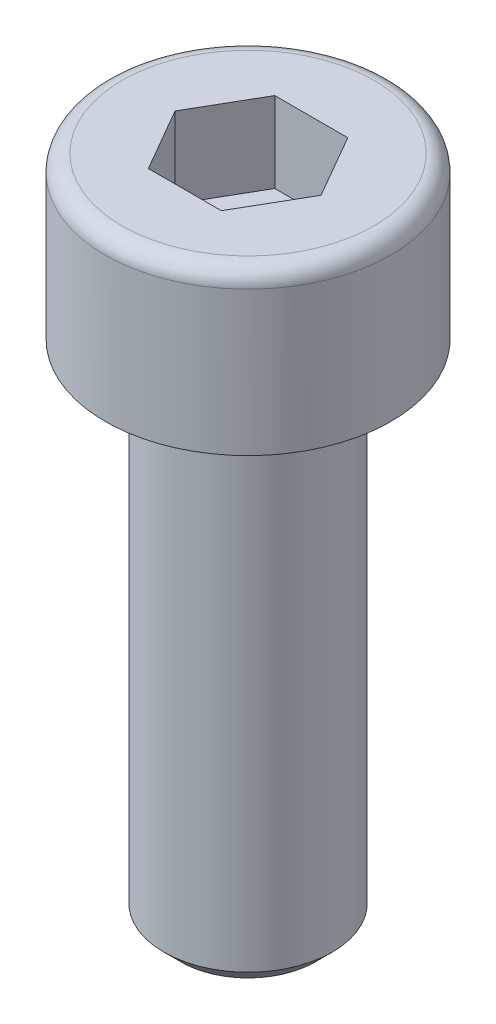
SolidWorks part; units mm, degrees
material "Cast Stainless Steel"
ref_plane "Front Plane" through (0, 0, 0) normal (0, 0, 1) x (1, 0, 0)
ref_plane "Top Plane" through (0, 0, 0) normal (0, 1, 0) x (1, 0, 0)
ref_plane "Right Plane" through (0, 0, 0) normal (1, 0, 0) x (0, 0, -1)
sketch "Sketch1" plane through (0, 0, 0) normal (0, 0, 1) x (1, 0, 0)
  line L0 (0, 0) -> (0, 3.82)
  line L1 (0, 3.82) -> (3.39, 3.82)
  line L2 (3.39, 3.82) -> (3.39, 0)
  line L3 (3.39, 0) -> (2, 0)
  line L4 (2, 0) -> (2, -12)
  line L5 (2, -12) -> (0, -12)
  line L6 (0, -12) -> (0, 0)
  line L7 (0, 3.82) -> (0, 12.7536) construction
  dimension "D1" = 12
  dimension "D2" = 3.82
  dimension "D3" = 4
  dimension "D4" = 6.78
revolve "Revolve1" add sketch "Sketch1" angle 360 about L7
chamfer "Chamfer1" distance 0.4 angle 45 1 edges at (0, -12, -2)
fillet "Fillet1" radius 0.4 1 edges at (0, 3.82, -3.39)
sketch "Sketch2" plane through (0, 3.82, 0) normal (0, 1, 0) x (1, 0, 0)
  line L1 (0.866, -1.5) -> (1.7321, 0)
  line L2 (1.7321, 0) -> (0.866, 1.5)
  line L3 (0.866, 1.5) -> (-0.866, 1.5)
  line L4 (-0.866, 1.5) -> (-1.7321, 0)
  line L5 (-1.7321, 0) -> (-0.866, -1.5)
  line L6 (-0.866, -1.5) -> (0.866, -1.5)
  circle A0 centre (0, 0) radius 1.5 construction
  dimension "D1" = 3
extrude "Cut-Extrude1" cut sketch "Sketch2" against normal blind 1.91
equation "\"d\"= 4"
equation "\"dk\"= 6.78"
equation "\"k\"= 3.82"
equation "\"s\"= 3"
equation "\"L\"= 12"
equation "\"D4@Sketch1\"=\"dk\""
equation "\"D2@Sketch1\"=\"k\""
equation "\"D1@Sketch1\"=\"L\""
equation "\"D3@Sketch1\"=\"d\""
equation "\"D1@Chamfer1\"=\"d\"/10"
equation "\"D1@Fillet1\"=\"d\"/10"
equation "\"D1@Sketch2\"=\"s\""
equation "\"D1@Cut-Extrude1\"=\"k\"/2"
